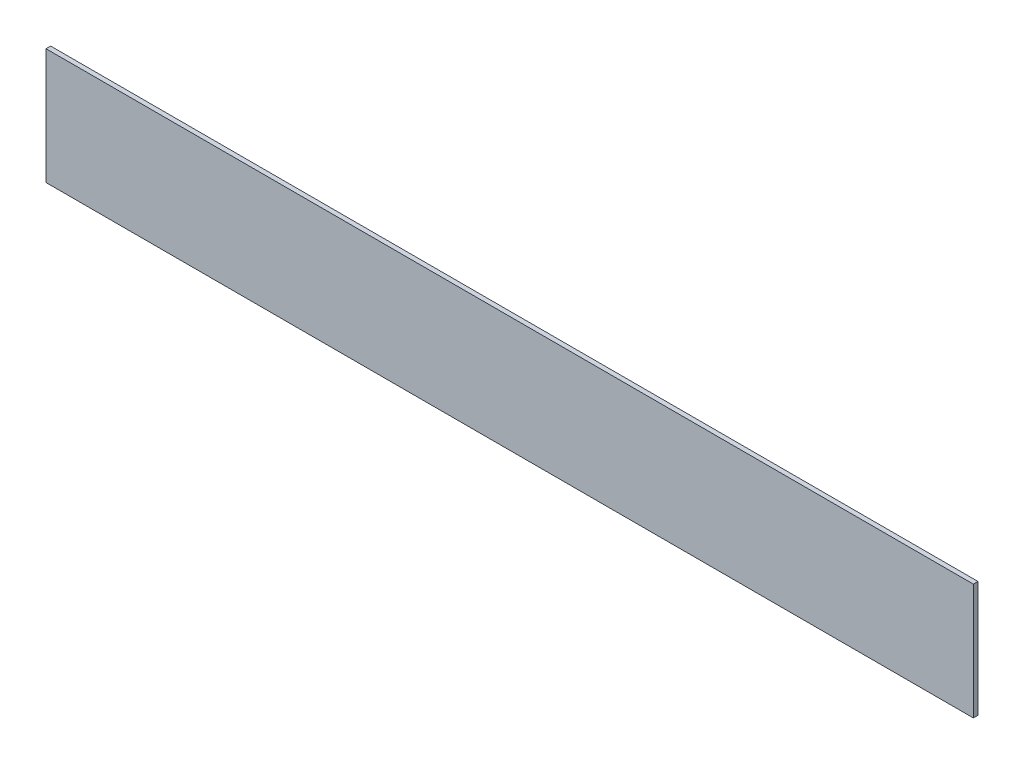
SolidWorks part; units mm, degrees
ref_plane "Front Plane" through (0, 0, 0) normal (0, 0, 1) x (1, 0, 0)
ref_plane "Top Plane" through (0, 0, 0) normal (0, 1, 0) x (1, 0, 0)
ref_plane "Right Plane" through (0, 0, 0) normal (1, 0, 0) x (0, 0, -1)
other "Configuration Table"
sketch "Sketch1" plane through (0, 0, 0) normal (0, 0, 1) x (1, 0, 0)
  line L1 (0, 1.6) -> (320, 1.6)
  line L2 (0, 1.6) -> (0, 41.6)
  line L3 (0, 41.6) -> (320, 41.6)
  line L4 (320, 1.6) -> (320, 41.6)
extrude "KUTU_duvar_on_1" add sketch "Sketch1" against normal blind 1.6 separate body
